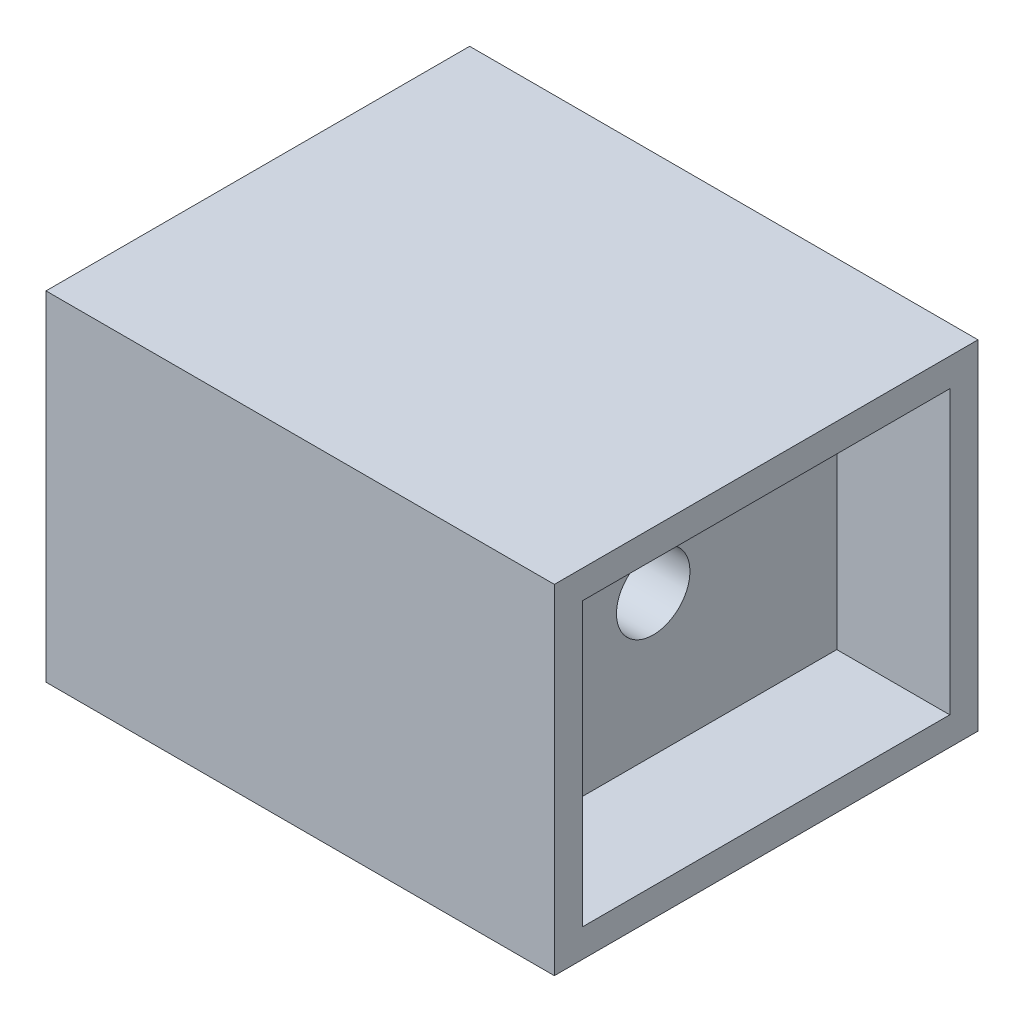
SolidWorks part; units mm, degrees
ref_plane "Plan de face" through (0, 0, 0) normal (0, 0, 1) x (1, 0, 0)
ref_plane "Plan de dessus" through (0, 0, 0) normal (0, 1, 0) x (1, 0, 0)
ref_plane "Plan de droite" through (0, 0, 0) normal (1, 0, 0) x (0, 0, -1)
sketch "Esquisse1" plane through (0, 0, 0) normal (1, 0, 0) x (0, 0, -1)
  line L1 (0, 0) -> (15, 0)
  line L2 (0, 0) -> (0, 12)
  line L3 (0, 12) -> (15, 12)
  line L4 (15, 0) -> (15, 12)
  dimension "D1" = 12
  dimension "D2" = 15
extrude "Boss.-Extru.1" add sketch "Esquisse1" along normal blind 4
sketch "Esquisse2" plane through (4, 0, 0) normal (1, 0, 0) x (0, 0, -1)
  line L1 (0, 12) -> (1, 12)
  line L2 (0, 12) -> (0, 0)
  line L3 (0, 0) -> (1, 0)
  line L4 (1, 12) -> (1, 0)
  line L5 (0, 0) -> (15, 0) construction
  line L6 (7.5, 12) -> (7.5, 0) construction
  line L7 (15, 12) -> (0, 12) construction
  line L8 (1, 6) -> (15, 6) construction
  line L9 (15, 0) -> (15, 12) construction
  line L10 (15, 0) -> (14, 0)
  line L11 (15, 12) -> (14, 12)
  line L12 (15, 12) -> (15, 0)
  line L13 (14, 12) -> (14, 0)
  dimension "D1" = 12
  dimension "D2" = 1
extrude "Boss.-Extru.2" add sketch "Esquisse2" along normal blind 4
sketch "Esquisse3" plane through (4, 0, 0) normal (1, 0, 0) x (0, 0, -1)
  line L0 (1, 6) -> (14, 6) construction
  line L1 (1, 12) -> (14, 12)
  line L2 (1, 12) -> (1, 11)
  line L3 (1, 11) -> (14, 11)
  line L4 (14, 12) -> (14, 11)
  line L5 (1, 0) -> (1, 12) construction
  line L6 (1, 0) -> (1, 1)
  line L7 (14, 0) -> (14, 1)
  line L8 (1, 0) -> (14, 0)
  line L9 (1, 1) -> (14, 1)
  dimension "D1" = 1
  dimension "D2" = 13
extrude "Boss.-Extru.3" add sketch "Esquisse3" along normal blind 4
sketch "Esquisse4" plane through (0, 0, 0) normal (-1, 0, 0) x (0, 0, 1)
  line L0 (-7.5, 0) -> (-7.5, 12) construction
  line L1 (0, 0) -> (-15, 0) construction
  line L2 (-15, 12) -> (0, 12) construction
  circle A0 centre (-7.5, 6) radius 1.3
extrude "Enlèv. mat.-Extru.1" cut sketch "Esquisse4" against normal through all
sketch "Esquisse5" plane through (0, 0, 0) normal (-1, 0, 0) x (0, 0, 1)
  circle A0 centre (-7.5, 6) radius 2.5
extrude "Enlèv. mat.-Extru.2" cut sketch "Esquisse5" against normal blind 1.5
chamfer "Chanfrein1" distance 1 angle 45 1 edges at (0, 6, -5)
sketch "Esquisse6" plane through (0, 0, 0) normal (-1, 0, 0) x (0, 0, 1)
  line L1 (0, 0) -> (-15, 0)
  line L2 (0, 0) -> (0, 2)
  line L3 (-2, 2) -> (-13, 2)
  line L4 (-15, 0) -> (-15, 2)
  line L5 (-15, 0) -> (-15, 12) construction
  line L7 (0, 0) -> (-2, 0)
  line L8 (0, 0) -> (0, 12)
  line L9 (0, 12) -> (-2, 12)
  line L10 (-2, 2) -> (-2, 10)
  line L11 (-15, 12) -> (0, 12) construction
  line L13 (-15, 12) -> (-13, 12)
  line L14 (-15, 12) -> (-15, 0)
  line L15 (-15, 0) -> (-13, 0)
  line L16 (-13, 10) -> (-13, 2)
  line L17 (-15, 12) -> (0, 12)
  line L18 (-15, 12) -> (-15, 10)
  line L19 (-13, 10) -> (-2, 10)
  line L20 (0, 12) -> (0, 10)
  line M2 (0, 0) -> (0, 12)
  line M3 (0, 12) -> (-15, 12)
  line M4 (-15, 12) -> (-15, 0)
  line M5 (-15, 0) -> (0, 0)
  dimension "D1" = 2
  dimension "D2" = 15
  dimension "D3" = 12
  dimension "D4" = 2
  dimension "D5" = 12
  dimension "D6" = 2
  dimension "D7" = 2
  dimension "D8" = 15
extrude "Boss.-Extru.4" add sketch "Esquisse6" along normal blind 10 contours L1 L8 L14 L16 L19 L10 L3 M5 M2 M3 M4
sketch "Esquisse7" plane through (-10, 0, 0) normal (-1, 0, 0) x (0, 0, 1)
  line L0 (-2, 10) -> (-1.9, 10) construction
  line L1 (-1.9, 10) -> (-1.9, 10.1) construction
  line L2 (-13, 2) -> (-13.1, 2) construction
  line L3 (-13.1, 2) -> (-13.1, 1.9) construction
  line L4 (-1.9, 10.1) -> (-13.1, 10.1)
  line L5 (-13.1, 10.1) -> (-13.1, 1.9)
  line L6 (-1.9, 10.1) -> (-1.9, 1.9)
  line L7 (-1.9, 1.9) -> (-13.1, 1.9)
extrude "Enlèv. mat.-Extru.3" cut sketch "Esquisse7" against normal blind 10
